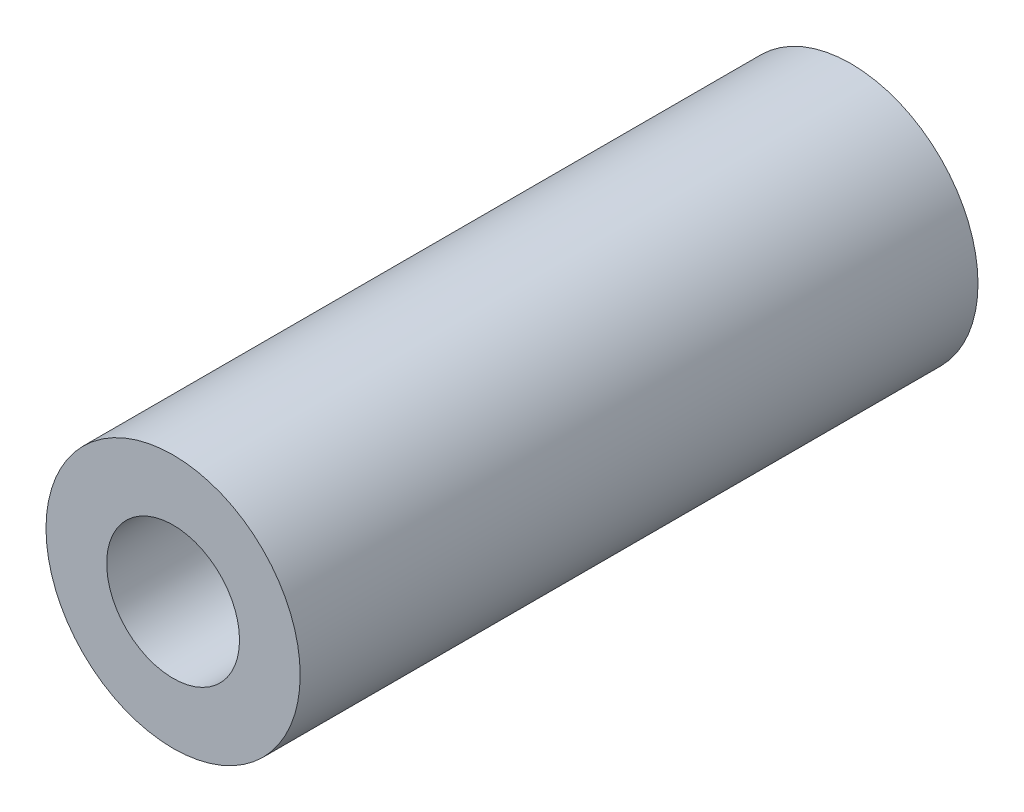
SolidWorks part; units mm, degrees
material "6061-T6 (SS)"
ref_plane "Front Plane" through (0, 0, 0) normal (0, 0, 1) x (1, 0, 0)
ref_plane "Top Plane" through (0, 0, 0) normal (0, 1, 0) x (1, 0, 0)
ref_plane "Right Plane" through (0, 0, 0) normal (1, 0, 0) x (0, 0, -1)
sketch "Sketch1" plane through (0, 0, 0) normal (0, 0, 1) x (1, 0, 0)
  circle A0 centre (0, 0) radius 2.4892
  circle A1 centre (0, 0) radius 4.7625
  dimension "D1" = 4.9784
  dimension "D2" = 9.525
extrude "Boss-Extrude1" add sketch "Sketch1" along normal blind 25.4
